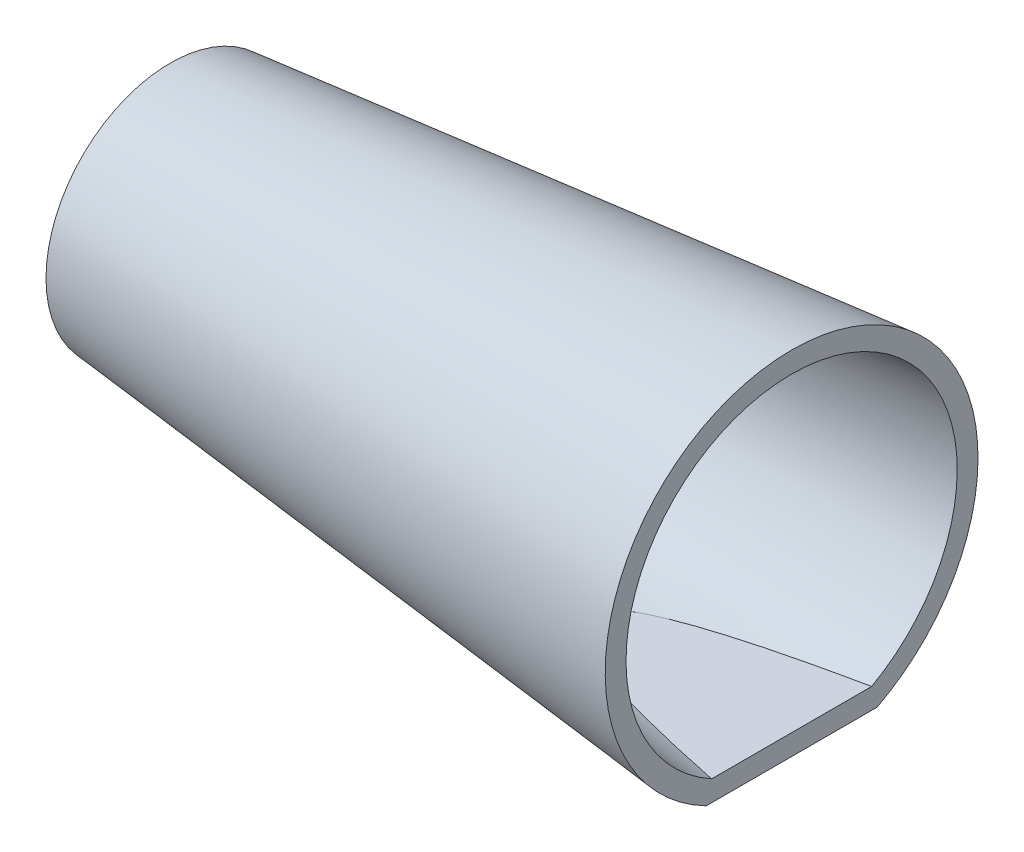
SolidWorks part; units mm, degrees
ref_plane "Front Plane" through (0, 0, 0) normal (0, 0, 1) x (1, 0, 0)
ref_plane "Top Plane" through (0, 0, 0) normal (0, 1, 0) x (1, 0, 0)
ref_plane "Right Plane" through (0, 0, 0) normal (1, 0, 0) x (0, 0, -1)
sketch "Sketch1" plane through (0, 0, 0) normal (0, 0, 1) x (1, 0, 0)
  line L0 (-78.5412, 0) -> (183.3998, 0) construction
  line L1 (-78.5412, 30) -> (71.4588, 45)
  line L2 (-78.5412, 24.9751) -> (71.4588, 39.9751)
  line L3 (-78.5412, 30) -> (-78.5412, 24.9751)
  line L4 (71.4588, 45) -> (71.4588, 39.9751)
  dimension "D1" = 5
  dimension "D2" = 30
  dimension "D3" = 45
  dimension "D4" = 150
revolve "Revolve1" add sketch "Sketch1" angle 360 about L0
sketch "Sketch3" plane through (71.4588, 0, 0) normal (1, 0, 0) x (0, 0, -1)
  line L0 (-20.6155, -40) -> (20.6155, -40)
  line L1 (-28.2843, -35) -> (28.2843, -35)
  circle A0 centre (0, 0) radius 45 construction
  arc A1 (-28.2843, -35) -> (-20.6155, -40) centre (0, 0) ccw
  arc A2 (20.6155, -40) -> (28.2843, -35) centre (0, 0) ccw
  dimension "D1" = 5
  dimension "D2" = 35
extrude "Boss-Extrude1" add sketch "Sketch3" against normal up to surface up to face at (-78.5412, 0, 30)
sketch "Sketch4" plane through (71.4588, 0, 0) normal (1, 0, 0) x (0, 0, -1)
  line L0 (-20.6155, -40) -> (20.6155, -40)
  circle A0 centre (0, 0) radius 45 construction
  arc A1 (-20.6155, -40) -> (20.6155, -40) centre (0, 0) ccw
extrude "Cut-Extrude1" cut sketch "Sketch4" against normal through all
